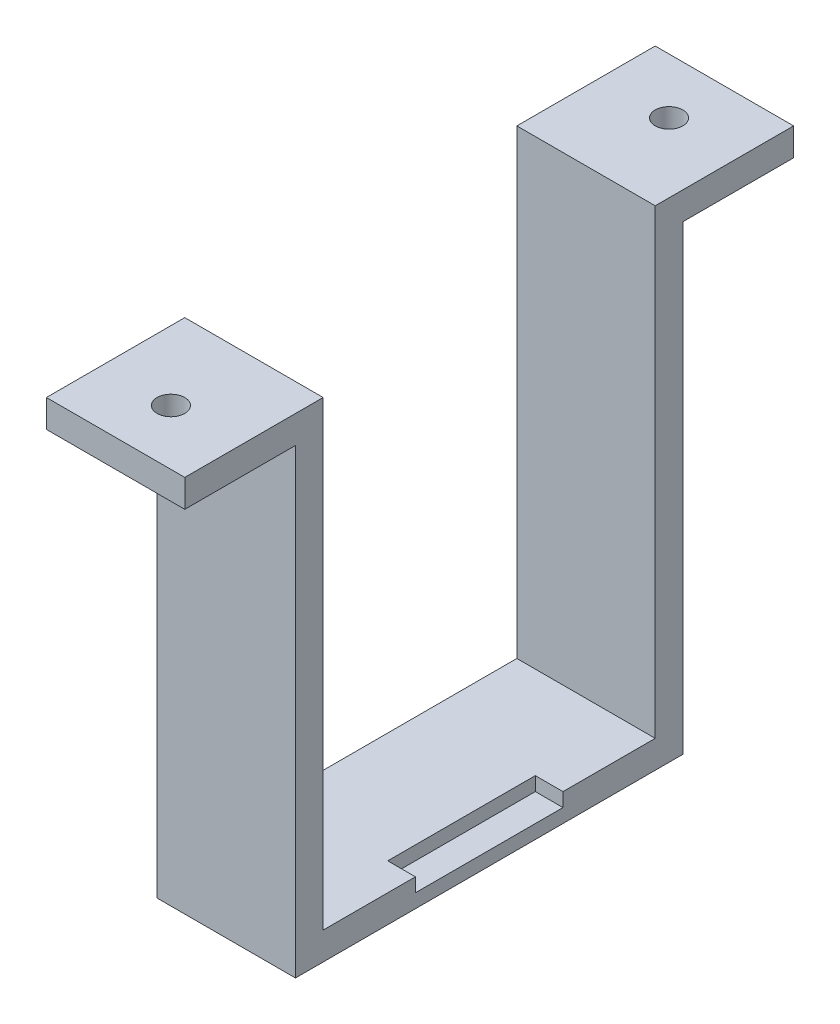
SolidWorks part; units mm, degrees
ref_plane "前视基准面" through (0, 0, 0) normal (0, 0, 1) x (1, 0, 0)
ref_plane "上视基准面" through (0, 0, 0) normal (0, 1, 0) x (1, 0, 0)
ref_plane "右视基准面" through (0, 0, 0) normal (1, 0, 0) x (0, 0, -1)
other "Configuration Table"
sketch "草图1" plane through (0, 0, 0) normal (1, 0, 0) x (0, 0, -1)
  line L0 (0, 0) -> (18, 0)
  line L1 (18, 0) -> (18, 50)
  line L2 (18, 50) -> (33, 50)
  line L3 (0, -3) -> (21, -3)
  line L4 (21, -3) -> (21, 47)
  line L5 (21, 47) -> (33, 47)
  line L6 (0, 0) -> (0, -3) construction
  line L7 (33, 50) -> (33, 47)
  line L8 (-33, 50) -> (-33, 47)
  line L9 (-21, 47) -> (-33, 47)
  line L10 (-21, -3) -> (-21, 47)
  line L11 (0, -3) -> (-21, -3)
  line L12 (-18, 50) -> (-33, 50)
  line L13 (-18, 0) -> (-18, 50)
  line L14 (0, 0) -> (-18, 0)
  dimension "D1" = 50
  dimension "D2" = 15
  dimension "D3" = 18
  dimension "D4" = 3
extrude "凸台-拉伸1" add sketch "草图1" along normal blind 15
sketch "草图2" plane through (0, 47, 0) normal (0, -1, 0) x (1, 0, 0)
  line L0 (0, -33) -> (15, -21) construction
  line L1 (15, -21) -> (15, -33) construction
  line L2 (0, -21) -> (15, -33) construction
  line L3 (0, 21) -> (15, 33) construction
  line L4 (0, 33) -> (15, 21) construction
  circle A0 centre (7.5, -27) radius 1.5
  circle A1 centre (7.5, 27) radius 1.5
  dimension "D1" = 3
  dimension "D2" = 3
extrude "切除-拉伸1" cut sketch "草图2" against normal up to next
sketch "草图3" plane through (15, 0, 0) normal (1, 0, 0) x (0, 0, -1)
  line L0 (18, 0) -> (-18, 0) construction
  line L1 (-8, 0) -> (8, 0)
  line L2 (-8, 0) -> (-8, -1.5)
  line L3 (-8, -1.5) -> (8, -1.5)
  line L4 (8, 0) -> (8, -1.5)
  line L5 (-8, 0) -> (-8, -3) construction
extrude "切除-拉伸2" cut sketch "草图3" against normal blind 3
